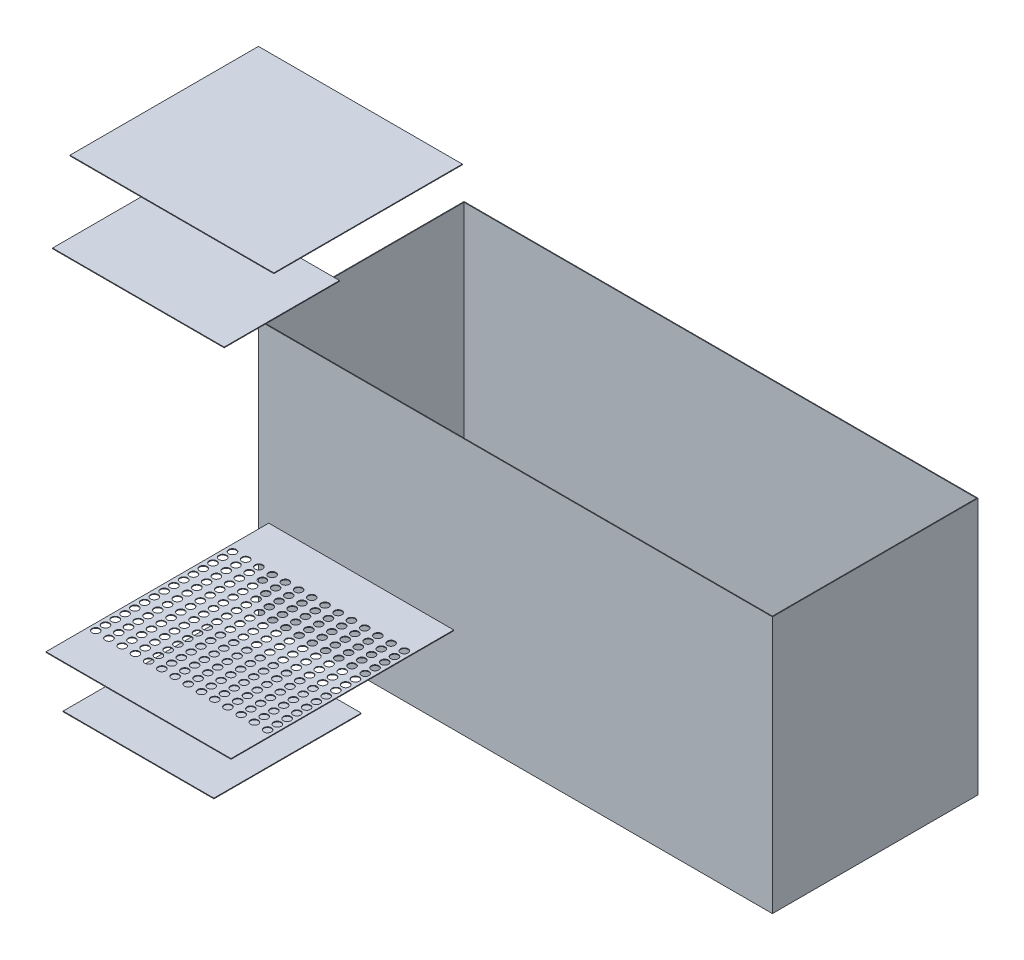
SolidWorks part; units mm, degrees
ref_plane "Спереди" through (0, 0, 0) normal (0, 0, 1) x (1, 0, 0)
ref_plane "Сверху" through (0, 0, 0) normal (0, 1, 0) x (1, 0, 0)
ref_plane "Справа" through (0, 0, 0) normal (1, 0, 0) x (0, 0, -1)
sketch "MASTER_FOOTPRINT" plane through (0, 0, 0) normal (0, 1, 0) x (1, 0, 0)
  line L1 (0, 0) -> (1500, 0)
  line L2 (0, 0) -> (0, 600)
  line L3 (0, 600) -> (1500, 600)
  line L4 (1500, 0) -> (1500, 600)
  dimension "D1" = 1500
  dimension "D2" = 600
extrude "BATH_BASE_PLATE" add sketch "MASTER_FOOTPRINT" along normal blind 750
shell "BATH_SHELL_2MM" thickness 2
sketch "Эскиз1" plane through (0, 0, 0) normal (0, 1, 0) x (1, 0, 0)
  line L1 (80, -220) -> (520, -220)
  line L2 (80, -220) -> (80, -650)
  line L3 (80, -650) -> (520, -650)
  line L4 (520, -220) -> (520, -650)
extrude "INLET_IMPACT_BAFFLE" add sketch "Эскиз1" along normal blind 2 from offset 125 separate body
sketch "Эскиз2" plane through (0, 0, 0) normal (0, 1, 0) x (1, 0, 0)
  line L0 (2, 2) -> (1498, 2) construction
  line L1 (30, 2) -> (570, 2)
  line L2 (30, 2) -> (30, -650)
  line L3 (30, -650) -> (570, -650)
  line L4 (570, 2) -> (570, -650)
  circle A0 centre (49.2857, -125) radius 11
  circle A1 centre (49.2857, -153.5) radius 11
  circle A2 centre (49.2857, -182) radius 11
  circle A3 centre (49.2857, -210.5) radius 11
  circle A4 centre (49.2857, -239) radius 11
  circle A5 centre (49.2857, -267.5) radius 11
  circle A6 centre (49.2857, -296) radius 11
  circle A7 centre (49.2857, -324.5) radius 11
  circle A8 centre (49.2857, -353) radius 11
  circle A9 centre (49.2857, -381.5) radius 11
  circle A10 centre (49.2857, -410) radius 11
  circle A11 centre (49.2857, -438.5) radius 11
  circle A12 centre (49.2857, -467) radius 11
  circle A13 centre (49.2857, -495.5) radius 11
  circle A14 centre (49.2857, -524) radius 11
  circle A15 centre (87.8571, -125) radius 11
  circle A16 centre (87.8571, -153.5) radius 11
  circle A17 centre (87.8571, -182) radius 11
  circle A18 centre (87.8571, -210.5) radius 11
  circle A19 centre (87.8571, -239) radius 11
  circle A20 centre (87.8571, -267.5) radius 11
  circle A21 centre (87.8571, -296) radius 11
  circle A22 centre (87.8571, -324.5) radius 11
  circle A23 centre (87.8571, -353) radius 11
  circle A24 centre (87.8571, -381.5) radius 11
  circle A25 centre (87.8571, -410) radius 11
  circle A26 centre (87.8571, -438.5) radius 11
  circle A27 centre (87.8571, -467) radius 11
  circle A28 centre (87.8571, -495.5) radius 11
  circle A29 centre (87.8571, -524) radius 11
  circle A30 centre (126.4286, -125) radius 11
  circle A31 centre (126.4286, -153.5) radius 11
  circle A32 centre (126.4286, -182) radius 11
  circle A33 centre (126.4286, -210.5) radius 11
  circle A34 centre (126.4286, -239) radius 11
  circle A35 centre (126.4286, -267.5) radius 11
  circle A36 centre (126.4286, -296) radius 11
  circle A37 centre (126.4286, -324.5) radius 11
  circle A38 centre (126.4286, -353) radius 11
  circle A39 centre (126.4286, -381.5) radius 11
  circle A40 centre (126.4286, -410) radius 11
  circle A41 centre (126.4286, -438.5) radius 11
  circle A42 centre (126.4286, -467) radius 11
  circle A43 centre (126.4286, -495.5) radius 11
  circle A44 centre (126.4286, -524) radius 11
  circle A45 centre (165, -125) radius 11
  circle A46 centre (165, -153.5) radius 11
  circle A47 centre (165, -182) radius 11
  circle A48 centre (165, -210.5) radius 11
  circle A49 centre (165, -239) radius 11
  circle A50 centre (165, -267.5) radius 11
  circle A51 centre (165, -296) radius 11
  circle A52 centre (165, -324.5) radius 11
  circle A53 centre (165, -353) radius 11
  circle A54 centre (165, -381.5) radius 11
  circle A55 centre (165, -410) radius 11
  circle A56 centre (165, -438.5) radius 11
  circle A57 centre (165, -467) radius 11
  circle A58 centre (165, -495.5) radius 11
  circle A59 centre (165, -524) radius 11
  circle A60 centre (203.5714, -125) radius 11
  circle A61 centre (203.5714, -153.5) radius 11
  circle A62 centre (203.5714, -182) radius 11
  circle A63 centre (203.5714, -210.5) radius 11
  circle A64 centre (203.5714, -239) radius 11
  circle A65 centre (203.5714, -267.5) radius 11
  circle A66 centre (203.5714, -296) radius 11
  circle A67 centre (203.5714, -324.5) radius 11
  circle A68 centre (203.5714, -353) radius 11
  circle A69 centre (203.5714, -381.5) radius 11
  circle A70 centre (203.5714, -410) radius 11
  circle A71 centre (203.5714, -438.5) radius 11
  circle A72 centre (203.5714, -467) radius 11
  circle A73 centre (203.5714, -495.5) radius 11
  circle A74 centre (203.5714, -524) radius 11
  circle A75 centre (242.1429, -125) radius 11
  circle A76 centre (242.1429, -153.5) radius 11
  circle A77 centre (242.1429, -182) radius 11
  circle A78 centre (242.1429, -210.5) radius 11
  circle A79 centre (242.1429, -239) radius 11
  circle A80 centre (242.1429, -267.5) radius 11
  circle A81 centre (242.1429, -296) radius 11
  circle A82 centre (242.1429, -324.5) radius 11
  circle A83 centre (242.1429, -353) radius 11
  circle A84 centre (242.1429, -381.5) radius 11
  circle A85 centre (242.1429, -410) radius 11
  circle A86 centre (242.1429, -438.5) radius 11
  circle A87 centre (242.1429, -467) radius 11
  circle A88 centre (242.1429, -495.5) radius 11
  circle A89 centre (242.1429, -524) radius 11
  circle A90 centre (280.7143, -125) radius 11
  circle A91 centre (280.7143, -153.5) radius 11
  circle A92 centre (280.7143, -182) radius 11
  circle A93 centre (280.7143, -210.5) radius 11
  circle A94 centre (280.7143, -239) radius 11
  circle A95 centre (280.7143, -267.5) radius 11
  circle A96 centre (280.7143, -296) radius 11
  circle A97 centre (280.7143, -324.5) radius 11
  circle A98 centre (280.7143, -353) radius 11
  circle A99 centre (280.7143, -381.5) radius 11
  circle A100 centre (280.7143, -410) radius 11
  circle A101 centre (280.7143, -438.5) radius 11
  circle A102 centre (280.7143, -467) radius 11
  circle A103 centre (280.7143, -495.5) radius 11
  circle A104 centre (280.7143, -524) radius 11
  circle A105 centre (319.2857, -125) radius 11
  circle A106 centre (319.2857, -153.5) radius 11
  circle A107 centre (319.2857, -182) radius 11
  circle A108 centre (319.2857, -210.5) radius 11
  circle A109 centre (319.2857, -239) radius 11
  circle A110 centre (319.2857, -267.5) radius 11
  circle A111 centre (319.2857, -296) radius 11
  circle A112 centre (319.2857, -324.5) radius 11
  circle A113 centre (319.2857, -353) radius 11
  circle A114 centre (319.2857, -381.5) radius 11
  circle A115 centre (319.2857, -410) radius 11
  circle A116 centre (319.2857, -438.5) radius 11
  circle A117 centre (319.2857, -467) radius 11
  circle A118 centre (319.2857, -495.5) radius 11
  circle A119 centre (319.2857, -524) radius 11
  circle A120 centre (357.8571, -125) radius 11
  circle A121 centre (357.8571, -153.5) radius 11
  circle A122 centre (357.8571, -182) radius 11
  circle A123 centre (357.8571, -210.5) radius 11
  circle A124 centre (357.8571, -239) radius 11
  circle A125 centre (357.8571, -267.5) radius 11
  circle A126 centre (357.8571, -296) radius 11
  circle A127 centre (357.8571, -324.5) radius 11
  circle A128 centre (357.8571, -353) radius 11
  circle A129 centre (357.8571, -381.5) radius 11
  circle A130 centre (357.8571, -410) radius 11
  circle A131 centre (357.8571, -438.5) radius 11
  circle A132 centre (357.8571, -467) radius 11
  circle A133 centre (357.8571, -495.5) radius 11
  circle A134 centre (357.8571, -524) radius 11
  circle A135 centre (396.4286, -125) radius 11
  circle A136 centre (396.4286, -153.5) radius 11
  circle A137 centre (396.4286, -182) radius 11
  circle A138 centre (396.4286, -210.5) radius 11
  circle A139 centre (396.4286, -239) radius 11
  circle A140 centre (396.4286, -267.5) radius 11
  circle A141 centre (396.4286, -296) radius 11
  circle A142 centre (396.4286, -324.5) radius 11
  circle A143 centre (396.4286, -353) radius 11
  circle A144 centre (396.4286, -381.5) radius 11
  circle A145 centre (396.4286, -410) radius 11
  circle A146 centre (396.4286, -438.5) radius 11
  circle A147 centre (396.4286, -467) radius 11
  circle A148 centre (396.4286, -495.5) radius 11
  circle A149 centre (396.4286, -524) radius 11
  circle A150 centre (435, -125) radius 11
  circle A151 centre (435, -153.5) radius 11
  circle A152 centre (435, -182) radius 11
  circle A153 centre (435, -210.5) radius 11
  circle A154 centre (435, -239) radius 11
  circle A155 centre (435, -267.5) radius 11
  circle A156 centre (435, -296) radius 11
  circle A157 centre (435, -324.5) radius 11
  circle A158 centre (435, -353) radius 11
  circle A159 centre (435, -381.5) radius 11
  circle A160 centre (435, -410) radius 11
  circle A161 centre (435, -438.5) radius 11
  circle A162 centre (435, -467) radius 11
  circle A163 centre (435, -495.5) radius 11
  circle A164 centre (435, -524) radius 11
  circle A165 centre (473.5714, -125) radius 11
  circle A166 centre (473.5714, -153.5) radius 11
  circle A167 centre (473.5714, -182) radius 11
  circle A168 centre (473.5714, -210.5) radius 11
  circle A169 centre (473.5714, -239) radius 11
  circle A170 centre (473.5714, -267.5) radius 11
  circle A171 centre (473.5714, -296) radius 11
  circle A172 centre (473.5714, -324.5) radius 11
  circle A173 centre (473.5714, -353) radius 11
  circle A174 centre (473.5714, -381.5) radius 11
  circle A175 centre (473.5714, -410) radius 11
  circle A176 centre (473.5714, -438.5) radius 11
  circle A177 centre (473.5714, -467) radius 11
  circle A178 centre (473.5714, -495.5) radius 11
  circle A179 centre (473.5714, -524) radius 11
  circle A180 centre (512.1429, -125) radius 11
  circle A181 centre (512.1429, -153.5) radius 11
  circle A182 centre (512.1429, -182) radius 11
  circle A183 centre (512.1429, -210.5) radius 11
  circle A184 centre (512.1429, -239) radius 11
  circle A185 centre (512.1429, -267.5) radius 11
  circle A186 centre (512.1429, -296) radius 11
  circle A187 centre (512.1429, -324.5) radius 11
  circle A188 centre (512.1429, -353) radius 11
  circle A189 centre (512.1429, -381.5) radius 11
  circle A190 centre (512.1429, -410) radius 11
  circle A191 centre (512.1429, -438.5) radius 11
  circle A192 centre (512.1429, -467) radius 11
  circle A193 centre (512.1429, -495.5) radius 11
  circle A194 centre (512.1429, -524) radius 11
  circle A195 centre (550.7143, -125) radius 11
  circle A196 centre (550.7143, -153.5) radius 11
  circle A197 centre (550.7143, -182) radius 11
  circle A198 centre (550.7143, -210.5) radius 11
  circle A199 centre (550.7143, -239) radius 11
  circle A200 centre (550.7143, -267.5) radius 11
  circle A201 centre (550.7143, -296) radius 11
  circle A202 centre (550.7143, -324.5) radius 11
  circle A203 centre (550.7143, -353) radius 11
  circle A204 centre (550.7143, -381.5) radius 11
  circle A205 centre (550.7143, -410) radius 11
  circle A206 centre (550.7143, -438.5) radius 11
  circle A207 centre (550.7143, -467) radius 11
  circle A208 centre (550.7143, -495.5) radius 11
  circle A209 centre (550.7143, -524) radius 11
extrude "DISTRIBUTOR_D22" add sketch "Эскиз2" along normal blind 2 from offset 250 separate body
sketch "Эскиз3" plane through (0, 0, 0) normal (0, 1, 0) x (1, 0, 0)
  line L0 (30, -650) -> (570, -650) construction
  line L1 (49.2857, -313.5) -> (550, -313.5)
  line L2 (49.2857, -313.5) -> (49.2857, -650)
  line L3 (49.2857, -650) -> (550, -650)
  line L4 (550, -313.5) -> (550, -650)
  circle A0 centre (49.2857, -324.5) radius 11 construction
extrude "OUTLET_SUBMERGED_BAFFLE" add sketch "Эскиз3" along normal blind 2 from offset 1280 separate body
sketch "Эскиз4" plane through (0, 0, 0) normal (0, 1, 0) x (1, 0, 0)
  line L1 (0, 0) -> (595, 0)
  line L2 (0, 0) -> (0, -550)
  line L3 (0, -550) -> (595, -550)
  line L4 (595, 0) -> (595, -550)
extrude "OVERFLOW_WEIR_Z550" add sketch "Эскиз4" along normal blind 2 from offset 1440 separate body
equation "\"AI_Q_Peak\"= 0.006"
equation "\"AI_B_Bath\" = 600"
equation "\"AI_L_Settle\" = 1050"
equation "\"AI_L_Inlet\"= 250"
equation "\"AI_L_Outlet\"= 200"
equation "\"AI_L_Bath\" = 1500"
equation "\"AI_H_Water\"= 550"
equation "\"AI_H_Freeboard\"= 200"
equation "\"AI_H_Bath\"= 750"
equation "\"AI_Shell_Thickness\"= 2"
equation "\"AI_Inlet_DN\"= 100"
equation "\"AI_Weir_Width\"= 600"
equation "\"AI_Inlet_Baffle_Offset\"= 125"
equation "\"AI_Distributor_Open_Area\"= 0.28"
equation "\"AI_Distributor_Hole_Dia\"= 22"
equation "\"AI_Distributor_Blind_Zone\"= 110"
equation "\"AI_Outlet_Baffle_Depth\"= 250"
equation "\"AI_Screw_Diameter\"= 100"
equation "\"AI_Screw_Pitch\"= 100"
equation "\"AI_Screw_Angle\"= 30"
equation "\"AI_Screw_Rpm\"= 15"
equation "\"AI_Screw_Clearance\"= 5"
equation "\"AI_Liner_Thickness\"= 5"
equation "\"AI_Discharge_Height\"= 650"
equation "\"AI_Frame_Height\"= 500"
equation "\"D1@MASTER_FOOTPRINT\" = \"AI_L_Bath\""
equation "\"D2@MASTER_FOOTPRINT\" = \"AI_B_Bath\""
equation "\"D1@BATH_BASE_PLATE\" = \"AI_H_Bath\""
